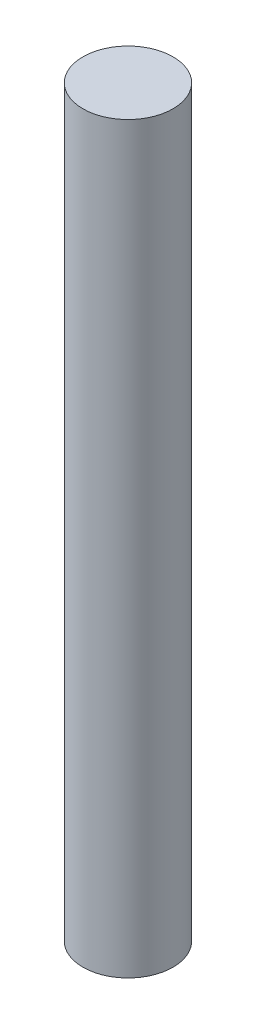
SolidWorks part; units mm, degrees
ref_plane "Front Plane" through (0, 0, 0) normal (0, 0, 1) x (1, 0, 0)
ref_plane "Top Plane" through (0, 0, 0) normal (0, 1, 0) x (1, 0, 0)
ref_plane "Right Plane" through (0, 0, 0) normal (1, 0, 0) x (0, 0, -1)
sketch "Sketch1" plane through (0, 0, 0) normal (0, 1, 0) x (1, 0, 0)
  circle A0 centre (0, 0) radius 1
  dimension "D1" = 2
extrude "Boss-Extrude1" add sketch "Sketch1" along normal blind 16.5
